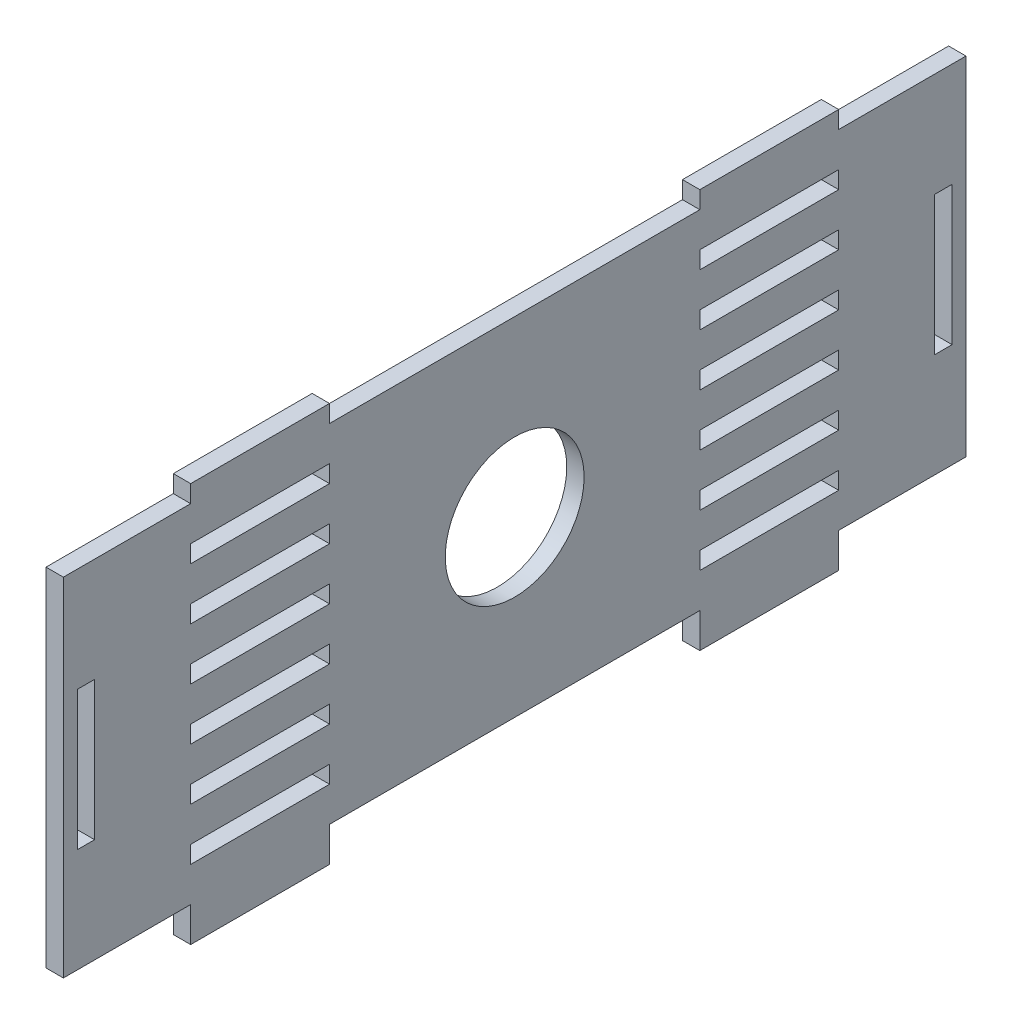
SolidWorks part; units mm, degrees
material "Maple"
ref_plane "Front Plane" through (0, 0, 0) normal (0, 0, 1) x (1, 0, 0)
ref_plane "Top Plane" through (0, 0, 0) normal (0, 1, 0) x (1, 0, 0)
ref_plane "Right Plane" through (0, 0, 0) normal (1, 0, 0) x (0, 0, -1)
sketch "Sketch1" plane through (0, 0, 0) normal (1, 0, 0) x (0, 0, -1)
  line L5 (-46.6667, -25) -> (-65, -25)
  line L6 (-46.6667, 25) -> (-65, 25)
  line L10 (46.6667, -25) -> (65, -25)
  line L11 (0, -12.7783) -> (0, 11.2959) construction
  line L12 (65, 25) -> (46.6667, 25)
  line L16 (-26.6667, -25) -> (-26.6667, -30)
  line L17 (-26.6667, -30) -> (-46.6667, -30)
  line L18 (-46.6667, -30) -> (-46.6667, -25)
  line L27 (-19.2126, 0) -> (21.2755, 0) construction
  line L35 (-46.6667, 27.5) -> (-46.6667, 25)
  line L36 (-26.6667, 27.5) -> (-46.6667, 27.5)
  line L37 (-26.6667, 25) -> (-26.6667, 27.5)
  line L43 (26.6667, 25) -> (26.6667, 27.5)
  line L44 (26.6667, 27.5) -> (46.6667, 27.5)
  line L45 (46.6667, 27.5) -> (46.6667, 25)
  line L61 (46.6667, -30) -> (46.6667, -25)
  line L62 (26.6667, -30) -> (46.6667, -30)
  line L63 (26.6667, -25) -> (26.6667, -30)
  line L67 (-65, 25) -> (-65, -25)
  line L69 (65, 25) -> (65, -25)
  line L75 (-63, 10) -> (-60.5, 10)
  line L76 (63, -10) -> (60.5, -10)
  line L77 (63, -10) -> (63, 10)
  line L78 (63, 10) -> (60.5, 10)
  line L79 (60.5, -10) -> (60.5, 10)
  line L80 (63, -10) -> (60.5, 10) construction
  line L81 (63, 10) -> (60.5, -10) construction
  line L82 (-60.5, -10) -> (-60.5, 10)
  line L83 (-63, -10) -> (-60.5, -10)
  line L84 (-63, -10) -> (-63, 10)
  line L85 (26.6667, -25) -> (-26.6667, -25)
  line L86 (-26.6667, 25) -> (26.6667, 25)
  circle A0 centre (0, 0) radius 10
  point P0 (0, 0)
  point P80 (61.75, 0)
  dimension "D8" = 20
  dimension "D9" = 2
  dimension "D10" = 53.3333
extrude "Boss-Extrude3" add sketch "Sketch1" along normal mid plane 2.5
sketch "Sketch2" plane through (1.25, 0, 0) normal (1, 0, 0) x (0, 0, -1)
  line L0 (-26.6667, 27.5) -> (-46.6667, 27.5) construction
  line L1 (-26.6667, 20) -> (-46.6667, 20)
  line L2 (-26.6667, 20) -> (-26.6667, 17.5)
  line L3 (-26.6667, 17.5) -> (-46.6667, 17.5)
  line L4 (-46.6667, 20) -> (-46.6667, 17.5)
  line L5 (-46.6667, 27.5) -> (-46.6667, 25) construction
  line L6 (-26.6667, 25) -> (26.6667, 25) construction
  line L7 (-26.6667, 12.5) -> (-46.6667, 12.5)
  line L8 (-26.6667, 12.5) -> (-26.6667, 10)
  line L9 (-46.6667, 12.5) -> (-46.6667, 10)
  line L10 (-26.6667, 10) -> (-46.6667, 10)
  line L11 (-26.6667, 5) -> (-46.6667, 5)
  line L12 (-26.6667, 5) -> (-26.6667, 2.5)
  line L13 (-46.6667, 5) -> (-46.6667, 2.5)
  line L14 (-26.6667, 2.5) -> (-46.6667, 2.5)
  line L15 (-26.6667, -2.5) -> (-46.6667, -2.5)
  line L16 (-26.6667, -2.5) -> (-26.6667, -5)
  line L17 (-46.6667, -2.5) -> (-46.6667, -5)
  line L18 (-26.6667, -5) -> (-46.6667, -5)
  line L19 (-26.6667, -10) -> (-46.6667, -10)
  line L20 (-26.6667, -10) -> (-26.6667, -12.5)
  line L21 (-46.6667, -10) -> (-46.6667, -12.5)
  line L22 (-26.6667, -12.5) -> (-46.6667, -12.5)
  line L24 (-26.6667, -17.5) -> (-46.6667, -17.5)
  line L25 (-26.6667, -17.5) -> (-26.6667, -20)
  line L26 (-46.6667, -17.5) -> (-46.6667, -20)
  line L27 (-26.6667, -20) -> (-46.6667, -20)
  line L28 (26.6667, -25) -> (-26.6667, -25) construction
  line L29 (0, 14.0123) -> (0, -13.7849) construction
  line L30 (26.6667, -17.5) -> (26.6667, -20)
  line L31 (26.6667, -20) -> (46.6667, -20)
  line L32 (46.6667, -17.5) -> (46.6667, -20)
  line L33 (26.6667, -17.5) -> (46.6667, -17.5)
  line L34 (26.6667, -10) -> (26.6667, -12.5)
  line L35 (26.6667, -12.5) -> (46.6667, -12.5)
  line L36 (46.6667, -10) -> (46.6667, -12.5)
  line L37 (26.6667, -10) -> (46.6667, -10)
  line L38 (26.6667, -2.5) -> (26.6667, -5)
  line L39 (26.6667, -5) -> (46.6667, -5)
  line L40 (46.6667, -2.5) -> (46.6667, -5)
  line L41 (26.6667, -2.5) -> (46.6667, -2.5)
  line L42 (26.6667, 5) -> (26.6667, 2.5)
  line L43 (26.6667, 2.5) -> (46.6667, 2.5)
  line L44 (46.6667, 5) -> (46.6667, 2.5)
  line L45 (26.6667, 5) -> (46.6667, 5)
  line L46 (26.6667, 12.5) -> (26.6667, 10)
  line L47 (26.6667, 10) -> (46.6667, 10)
  line L48 (46.6667, 12.5) -> (46.6667, 10)
  line L49 (26.6667, 12.5) -> (46.6667, 12.5)
  line L50 (26.6667, 17.5) -> (46.6667, 17.5)
  line L51 (46.6667, 20) -> (46.6667, 17.5)
  line L52 (26.6667, 20) -> (46.6667, 20)
  line L53 (26.6667, 20) -> (26.6667, 17.5)
  dimension "D1" = 5
  dimension "D3" = 5
  dimension "D2" = 6
extrude "Cut-Extrude1" cut sketch "Sketch2" against normal through all
